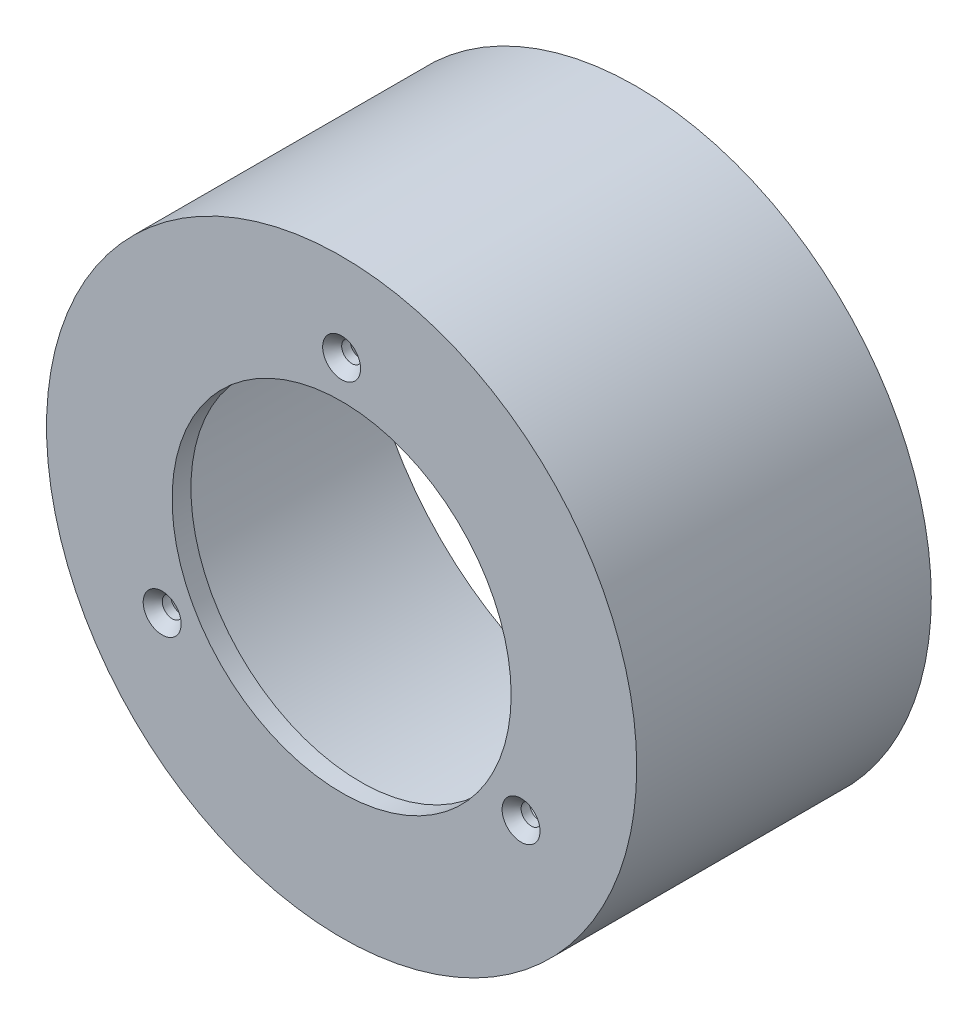
SolidWorks part; units mm, degrees
material "6061-T6 (SS)"
ref_plane "Front Plane" through (0, 0, 0) normal (0, 0, 1) x (1, 0, 0)
ref_plane "Top Plane" through (0, 0, 0) normal (0, 1, 0) x (1, 0, 0)
ref_plane "Right Plane" through (0, 0, 0) normal (1, 0, 0) x (0, 0, -1)
sketch "Sketch1" plane through (0, 0, 0) normal (0, 0, 1) x (1, 0, 0)
  circle A0 centre (0, 0) radius 20.5
  circle A1 centre (0, 0) radius 13.5
  circle A2 centre (0, 16.5) radius 1.5875
  circle A3 centre (14.2894, -8.25) radius 1.5875
  circle A4 centre (-14.2894, -8.25) radius 1.5875
  circle A5 centre (0, 0) radius 16.5 construction
  dimension "D1" = 27
  dimension "D2" = 3.175
  dimension "D4" = 41
  dimension "D3" = 33
extrude "Extrude1" add sketch "Sketch1" along normal blind 1.5 contours A2 | A3 | A0 A4 A3 A2 A1 | A4
sketch "Sketch4" plane through (0, 0, 1.5) normal (0, 0, 1) x (1, 0, 0)
  circle A0 centre (0, 0) radius 23.5
  circle A1 centre (0, 0) radius 20.5
  circle A2 centre (0, 0) radius 20.5
  dimension "D1" = 0
  dimension "D2" = 3
extrude "Boss-Extrude3" add sketch "Sketch4" against normal up to surface (1.5 mm away) up to face at (13.5, 0, 0)
sketch "Sketch5" plane through (0, 0, 0) normal (0, 0, -1) x (-1, 0, 0)
  circle A0 centre (0, 0) radius 22
  circle A1 centre (0, 0) radius 23.5
  circle A2 centre (0, 0) radius 23.5
  dimension "D1" = 0
  dimension "D2" = 1.5
extrude "Boss-Extrude5" add sketch "Sketch5" along normal blind 21.9577
sketch "Sketch8" plane through (0, 0, 1.5) normal (0, 0, 1) x (1, 0, 0)
  circle A0 centre (0, 0) radius 16.5
  circle A1 centre (0, 0) radius 23.5
  circle A2 centre (0, 0) radius 23.5
  point P1 (0, 16.5)
  point P5 (14.2894, -8.25)
  point P8 (-14.2894, -8.25)
  point P10 (14.2894, 8.25)
  point P11 (14.2894, -8.25)
  point P12 (0, -16.5)
  point P13 (-14.2894, -8.25)
  point P14 (-14.2894, 8.25)
  dimension "D2" = 33
  dimension "D1" = 0
  dimension "D3" = 3
  dimension "D4" = 6
sketch "Sketch10" plane through (0, 0, 0) normal (0, 1, 0) x (1, 0, 0)
  line L0 (0, 0) -> (0, 12.0091) construction
  line L1 (0, 12.0091) -> (-23.5879, 12.0091)
  line L2 (-23.5879, 12.0091) -> (-23.5, -1.5)
  line L3 (-23.5, -1.5) -> (23.5, -1.5) construction
  line L4 (-23.5, -1.5) -> (0, -1.5)
  line L5 (-13.5, -1.5) -> (13.5, -1.5) construction
  line L6 (0, -1.5) -> (0, 0)
  line L7 (-9, 12.0091) -> (-9, -1.5)
  line L8 (-9, 12.0091) -> (-13.5201, -1.5)
  dimension "D1" = 12.0091
  dimension "D2" = 9
  dimension "D3" = 18.5
revolve "Cut-Revolve1" [suppressed] cut sketch "Sketch10" angle 360 about L0
hole_wizard "CSK for #0 Flat Head Machine Screw1" positions "3DSketch1" profile "Sketch11" countersink size "#0" standard "Ansi Inch" end condition through all
sketch3d "3DSketch1"
  point P0 (0, 16.5, 1.5)
  point P3 (14.2894, -8.25, 1.5)
  point P6 (-14.2894, -8.25, 1.5)
sketch "Sketch11" plane through (0, 16.5, 1.5) normal (1, 0, 0) x (0, -1, 0)
  line L0 (0, 0) -> (0, 23.4577)
  line L1 (0, 23.4577) -> (0.8064, 23.4577)
  line L2 (0.8064, 23.4577) -> (0.8064, 0.8108)
  line L3 (0.8064, 0.8108) -> (1.5113, 0)
  line L5 (1.5113, 0) -> (0, 0)
  line L6 (-0.8064, 0.8108) -> (-1.5113, 0) construction
  line L11 (0, -6.35) -> (0, 107.95) construction
  dimension "Thru Hole Dia." = 1.6129
  dimension "Thru Hole Depth" = 23.4577
  dimension "Near C'Sink Dia." = 3.0226
  dimension "Near C'Sink Angle" = 82
